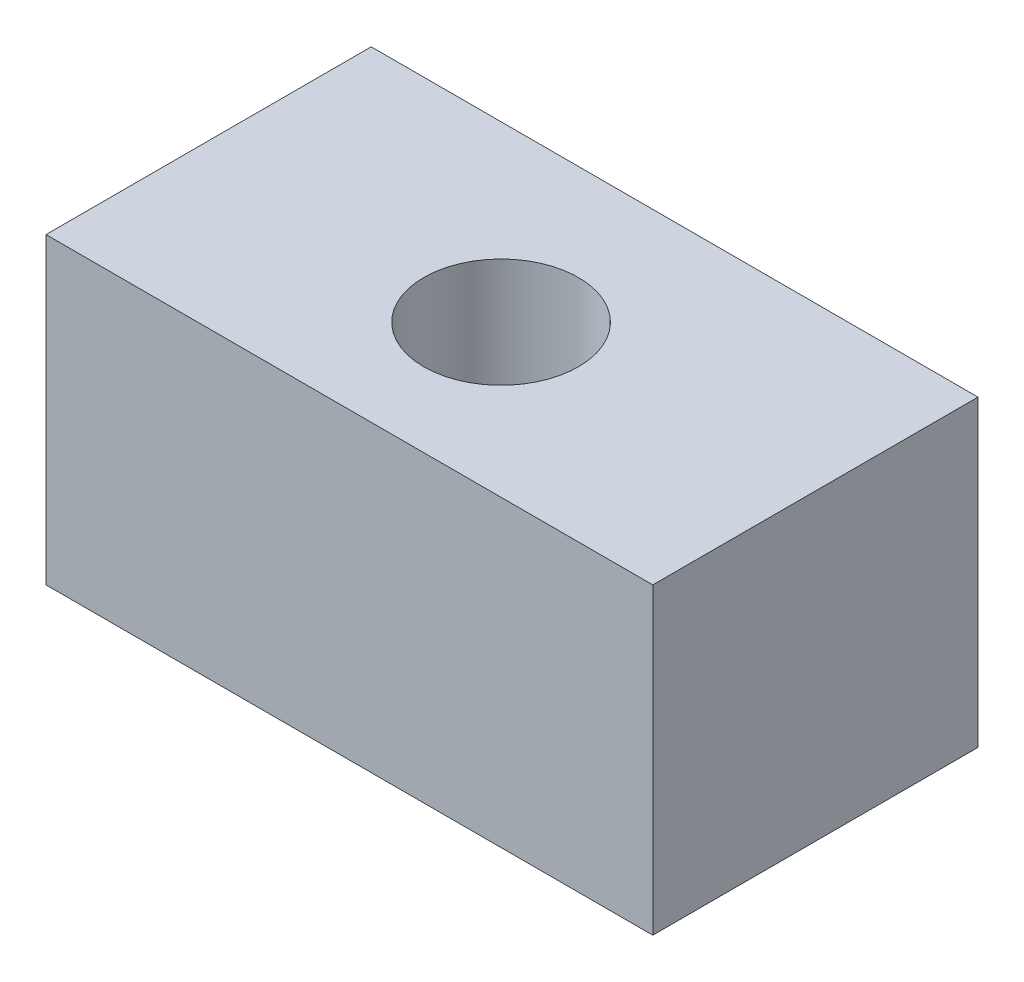
SolidWorks part; units mm, degrees
ref_plane "Front Plane" through (0, 0, 0) normal (0, 0, 1) x (1, 0, 0)
ref_plane "Top Plane" through (0, 0, 0) normal (0, 1, 0) x (1, 0, 0)
ref_plane "Right Plane" through (0, 0, 0) normal (1, 0, 0) x (0, 0, -1)
sketch "Sketch1" plane through (0, 0, 0) normal (0, 0, 1) x (1, 0, 0)
  line L1 (-25.4, 12.7) -> (25.4, 12.7)
  line L2 (-25.4, 12.7) -> (-25.4, -12.7)
  line L3 (-25.4, -12.7) -> (25.4, -12.7)
  line L4 (25.4, 12.7) -> (25.4, -12.7)
  dimension "D1" = 50.8
  dimension "D2" = 25.4
  dimension "D3" = 12.7
  dimension "D4" = 25.4
extrude "Boss-Extrude1" add sketch "Sketch1" along normal blind 27.2288
sketch "Sketch2" plane through (0, 12.7, 0) normal (0, 1, 0) x (1, 0, 0)
  line L1 (25.4, -27.2288) -> (-25.4, -27.2288) construction
  line L2 (-25.4, -27.2288) -> (-25.4, 0) construction
  circle A0 centre (0, -14.5288) radius 6.477
  dimension "D1" = 12.954
  dimension "D2" = 12.7
  dimension "D3" = 25.4
extrude "Cut-Extrude1" cut sketch "Sketch2" against normal blind 15.24
